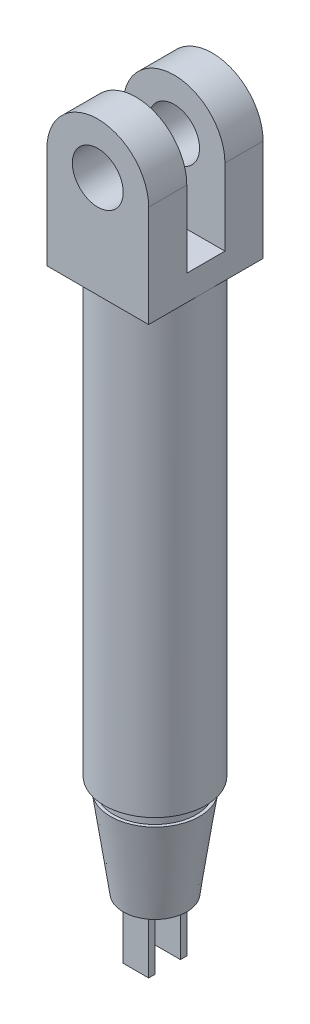
SolidWorks part; units mm, degrees
ref_plane "前视基准面" through (0, 0, 0) normal (0, 0, 1) x (1, 0, 0)
ref_plane "上视基准面" through (0, 0, 0) normal (0, 1, 0) x (1, 0, 0)
ref_plane "右视基准面" through (0, 0, 0) normal (1, 0, 0) x (0, 0, -1)
sketch "草图1" plane through (0, 0, 0) normal (0, 0, 1) x (1, 0, 0)
  line L0 (0, 0) -> (0, 70) construction
  line L1 (8, 70) -> (0, 70)
  line L2 (8, 70) -> (8, 0)
  line L3 (8, 0) -> (6.5, 0)
  line L4 (6.5, 0) -> (6.5, -2)
  line L5 (6.5, -2) -> (7, -2)
  line L6 (7, -2) -> (5, -16)
  line L7 (0, 0) -> (0, -16) construction
  line L8 (0, -16) -> (5, -16)
  line L9 (0, 70) -> (0, -16)
  dimension "D1" = 5
  dimension "D2" = 14
  dimension "D3" = 7
  dimension "D4" = 8
  dimension "D5" = 6.5
  dimension "D6" = 70
  dimension "D7" = 2
  dimension "D8" = 1.5
revolve "旋转1" add sketch "草图1" angle 360 about L9
sketch "草图2" plane through (0, 70, 0) normal (0, 1, 0) x (1, 0, 0)
  line L1 (-8, 9) -> (8, 9)
  line L2 (-8, 9) -> (-8, -9)
  line L3 (-8, -9) -> (8, -9)
  line L4 (8, 9) -> (8, -9)
  line L5 (-8, 9) -> (8, -9) construction
  line L6 (-8, -9) -> (8, 9) construction
  point P0 (0, 0)
  dimension "D1" = 18
  dimension "D2" = 16
extrude "凸台-拉伸1" add sketch "草图2" along normal blind 4
sketch "草图3" plane through (0, 0, 0) normal (0, 0, 1) x (1, 0, 0)
  line L0 (0, 74) -> (0, 86) construction
  line L1 (-8, 74) -> (8, 74) construction
  line L2 (-8, 74) -> (-8, 86)
  line L3 (8, 86) -> (8, 74)
  line L4 (-8, 74) -> (8, 74)
  circle A0 centre (0, 86) radius 4
  arc A1 (-8, 86) -> (8, 86) centre (0, 86) cw
  dimension "D2" = 8
  dimension "D1" = 12
extrude "凸台-拉伸3" add sketch "草图3" along normal blind 6 from offset 3
mirror "镜向1" about plane through (0, 0, 0) normal (0, 0, 1) of "凸台-拉伸3"
sketch "草图4" plane through (0, 0, 0) normal (0, 0, 1) x (1, 0, 0)
  line L0 (0, -16) -> (0, 0) construction
  line L1 (-5, -16) -> (5, -16) construction
  line L3 (-2, -16) -> (2, -16)
  line L4 (-2, -16) -> (-2, -25)
  line L5 (-2, -25) -> (2, -25)
  line L6 (2, -16) -> (2, -25)
  dimension "D1" = 9
  dimension "D2" = 4
extrude "凸台-拉伸4" add sketch "草图4" along normal blind 1 from offset 2
mirror "镜向2" about plane through (0, 0, 0) normal (0, 0, 1) of "凸台-拉伸4"
